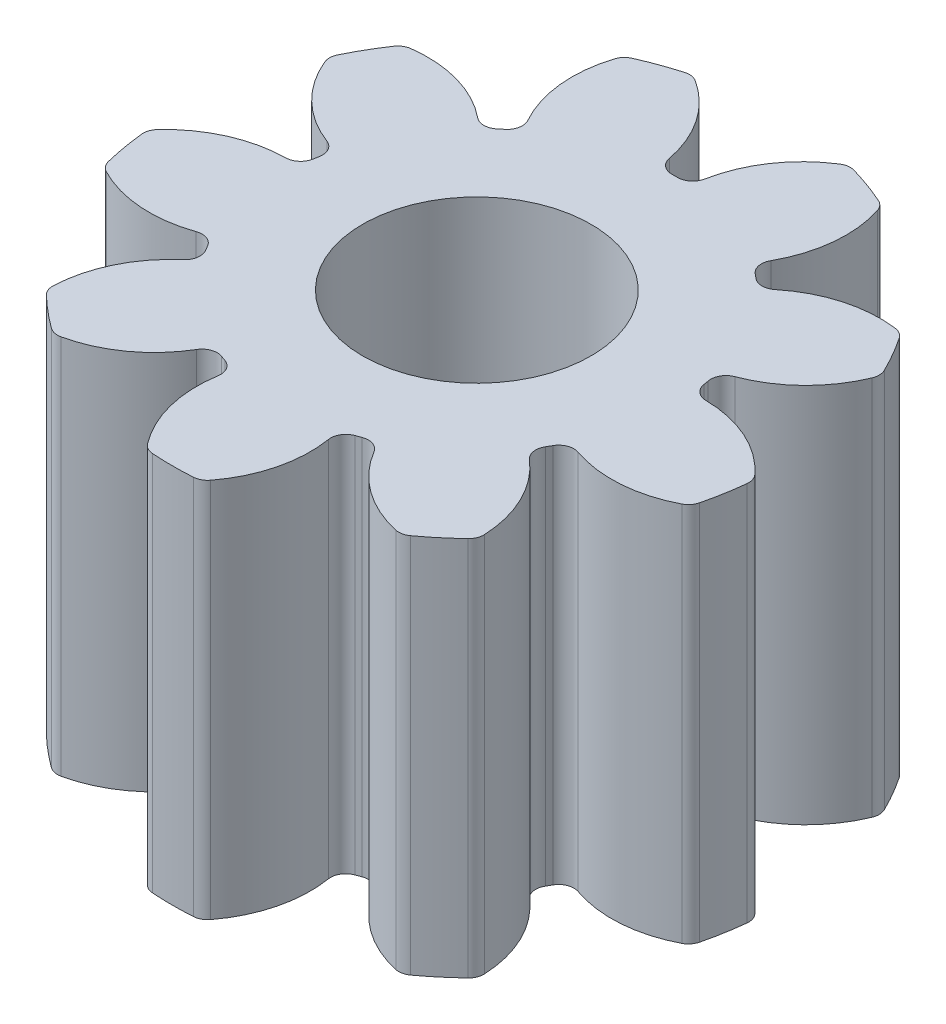
SolidWorks part; units mm, degrees
ref_plane "Front Plane" through (0, 0, 0) normal (0, 0, 1) x (1, 0, 0)
ref_plane "Top Plane" through (0, 0, 0) normal (0, 1, 0) x (1, 0, 0)
ref_plane "Right Plane" through (0, 0, 0) normal (1, 0, 0) x (0, 0, -1)
sketch "Sketch1" plane through (0, 0, 0) normal (0, 1, 0) x (1, 0, 0)
  circle A0 centre (0, 0) radius 2
  circle A1 centre (0, 0) radius 0.75
  dimension "D1" = 4
  dimension "D2" = 1.5
extrude "Boss-Extrude1" add sketch "Sketch1" along normal blind 2.5
sketch "Sketch2" plane through (0, 2.5, 0) normal (0, 1, 0) x (1, 0, 0)
  line L0 (0, 0) -> (0, 2.1618) construction
  line L1 (0, 0) -> (0.7463, 2.0506) construction
  line L2 (-0.3126, 1.7727) -> (0.3126, 1.7727) construction
  line L3 (0.3126, 1.7727) -> (0.9, 1.5588) construction
  line L4 (-0.56, 2.6289) -> (0, 1.0903) construction
  line L5 (0, 0) -> (-0.1053, 1.2957) construction
  circle A0 centre (0, 0) radius 1.3 construction
  circle A1 centre (0, 0) radius 1.8 construction
  circle A2 centre (0, 0) radius 2 construction
  circle A3 centre (0, 0) radius 2 construction
  arc A4 (-0.5141, 1.9328) -> (-0.1053, 1.2957) centre (-0.9079, 1.2305) cw
  arc A5 (0.5141, 1.9328) -> (0.1053, 1.2957) centre (0.9079, 1.2305) ccw
  arc A6 (-0.5141, 1.9328) -> (0.5141, 1.9328) centre (0, 0) cw
  arc A7 (-0.1053, 1.2957) -> (0.1053, 1.2957) centre (0, 0) cw
  dimension "D1" = 3.6
  dimension "D2" = 2.6
  dimension "D3" = 20
  dimension "D4" = 20
extrude "Cut-Extrude1" cut sketch "Sketch2" against normal through all
pattern_circular "CirPattern1" count 9 over 360 about axis through (0, 0, 0) along (0, 1, 0) of "Cut-Extrude1"
fillet "Fillet1" radius 0.1 36 edges at (-1.0695, 1.25, 0.7391) (-0.5421, 1.25, 1.1816) (-1.4168, 1.25, 1.4116) (-1.1441, 1.25, 1.6404) (1.8142, 1.25, -0.8419) (0.1053, 1.25, -1.2957) (-0.1053, 1.25, -1.2957) (0.9136, 1.25, -0.9249) (0.7522, 1.25, -1.0603) (1.2943, 1.25, -0.1213) (1.0695, 1.25, 0.7391) (1.2578, 1.25, -0.3287) (1.9927, 1.25, 0.1706) (1.9309, 1.25, 0.5212) (1.1748, 1.25, 0.5566) (1.4168, 1.25, 1.4116) (0.3442, 1.25, 1.2536) (0.178, 1.25, 1.9921) (1.1441, 1.25, 1.6404) (0.5421, 1.25, 1.1816) (-1.1748, 1.25, 0.5566) (-0.3442, 1.25, 1.2536) (-0.178, 1.25, 1.9921) (1.6362, 1.25, -1.1502) (0.8486, 1.25, -1.811) (0.5141, 1.25, -1.9328) (-0.5141, 1.25, -1.9328) (-1.9309, 1.25, 0.5212) (-1.2578, 1.25, -0.3287) (-0.9136, 1.25, -0.9249) (-1.2943, 1.25, -0.1213) (-1.9927, 1.25, 0.1706) (-1.8142, 1.25, -0.8419) (-1.6362, 1.25, -1.1502) (-0.7522, 1.25, -1.0603) (-0.8486, 1.25, -1.811)
